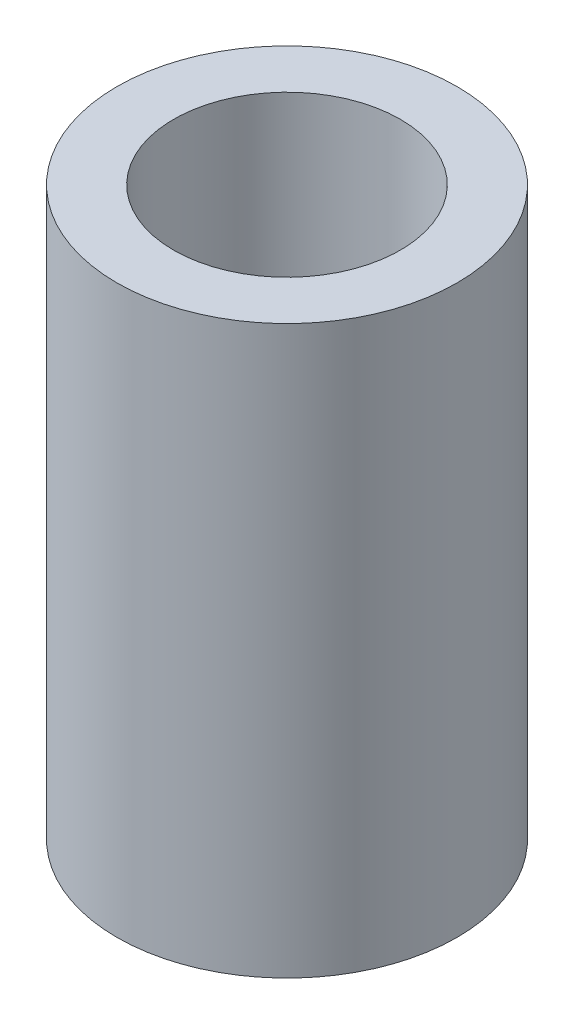
SolidWorks part; units mm, degrees
ref_plane "Front Plane" through (0, 0, 0) normal (0, 0, 1) x (1, 0, 0)
ref_plane "Top Plane" through (0, 0, 0) normal (0, 1, 0) x (1, 0, 0)
ref_plane "Right Plane" through (0, 0, 0) normal (1, 0, 0) x (0, 0, -1)
sketch "Sketch1" plane through (0, 0, 0) normal (0, 1, 0) x (1, 0, 0)
  circle A0 centre (0, 0) radius 3.81
extrude "Boss-Extrude2" add sketch "Sketch1" along normal blind 12.7
sketch "Sketch3" plane through (0, 12.7, 0) normal (0, 1, 0) x (1, 0, 0)
  circle A0 centre (0, 0) radius 2.54
extrude "Cut-Extrude2" cut sketch "Sketch3" against normal blind 12.7
